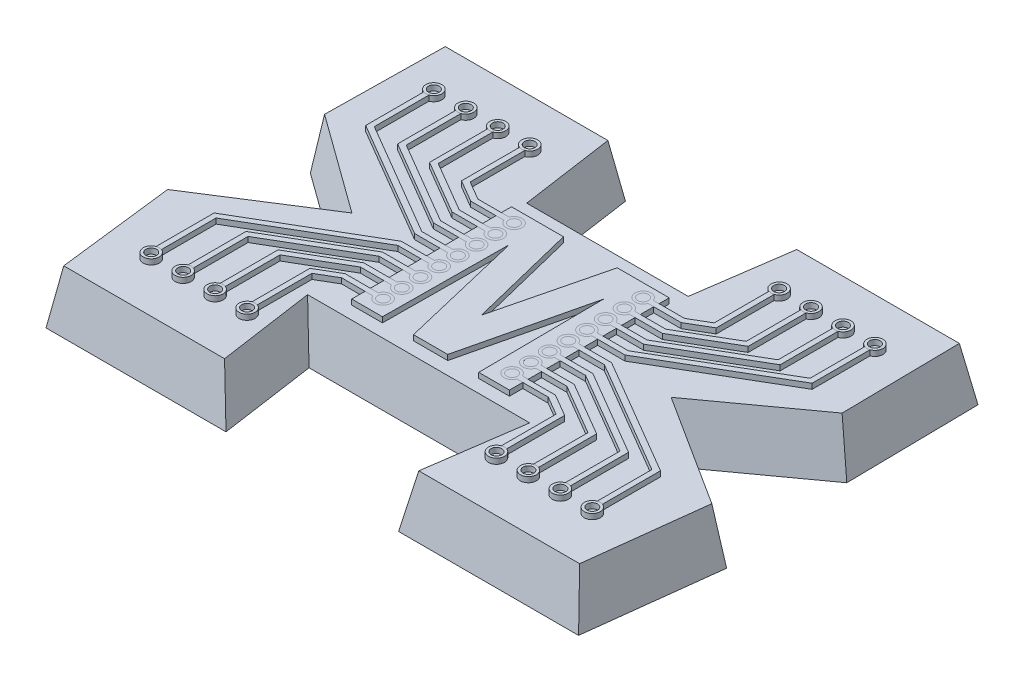
SolidWorks part; units mm, degrees
ref_plane "Спереди" through (0, 0, 0) normal (0, 0, 1) x (1, 0, 0)
ref_plane "Сверху" through (0, 0, 0) normal (0, 1, 0) x (1, 0, 0)
ref_plane "Справа" through (0, 0, 0) normal (1, 0, 0) x (0, 0, -1)
sketch "Эскиз1" plane through (0, 0, 0) normal (0, 1, 0) x (1, 0, 0)
  line L0 (0, 0) -> (-5.9483, 49.6449)
  line L1 (-5.9483, 49.6449) -> (33.7998, 75)
  line L2 (33.7998, 75) -> (-0.7287, 100.0053)
  line L3 (-0.7287, 100.0053) -> (0, 150)
  line L4 (0, 150) -> (67.5996, 150)
  line L5 (67.5996, 150) -> (72.7258, 114.3707)
  line L6 (72.7258, 114.3707) -> (127.2742, 114.3707)
  line L7 (0, 0) -> (67.5996, 0)
  line L8 (67.5996, 0) -> (62.3599, 36.418)
  line L9 (62.3599, 36.418) -> (137.6401, 36.418)
  line L10 (100, 114.3707) -> (100, 36.418) construction
  line L11 (33.7998, 0) -> (33.7998, 150) construction
  line L12 (166.2002, 0) -> (166.2002, 150) construction
  line L13 (132.4004, 0) -> (137.6401, 36.418)
  line L14 (200, 0) -> (132.4004, 0)
  line L15 (132.4004, 150) -> (127.2742, 114.3707)
  line L16 (200, 150) -> (132.4004, 150)
  line L17 (200.7287, 100.0053) -> (200, 150)
  line L18 (166.2002, 75) -> (200.7287, 100.0053)
  line L19 (205.9483, 49.6449) -> (166.2002, 75)
  line L20 (200, 0) -> (205.9483, 49.6449)
  dimension "D1" = 100
  dimension "D3" = 150
  dimension "D4" = 50
extrude "X" add sketch "Эскиз1" along normal blind 20 draft 10
sketch "Эскиз6" plane through (0, 20, 0) normal (0, 1, 0) x (1, 0, 0)
  line L0 (70, 104.8152) -> (70, 44.8152)
  line L1 (99.6154, 63.8897) -> (99.6154, 44.8152) construction
  line L2 (70, 44.8152) -> (81.5385, 44.8152)
  line L3 (81.5385, 44.8152) -> (81.9231, 92.0507)
  line L4 (81.9231, 92.0507) -> (93.1851, 44.8152)
  line L5 (70, 123.5265) -> (124.007, 123.5265) construction
  line L6 (93.1851, 44.8152) -> (106.0457, 44.8152)
  line L7 (106.0457, 44.8152) -> (117.3077, 92.0507)
  line L8 (117.3077, 92.0507) -> (117.6923, 44.8152)
  line L9 (117.6923, 44.8152) -> (129.2308, 44.8152)
  line L10 (129.2308, 44.8152) -> (129.2308, 104.8152)
  line L11 (70, 123.5265) -> (70, 26.4735) construction
  line L12 (70, 26.4735) -> (124.007, 26.4735) construction
  line L13 (129.2308, 104.8152) -> (109.7115, 104.8152)
  line L14 (109.7115, 104.8152) -> (99.6154, 63.8897)
  line L15 (99.6154, 63.8897) -> (89.5192, 104.8152)
  line L16 (89.5192, 104.8152) -> (70, 104.8152)
  line L17 (124.007, 123.5265) -> (124.007, 26.4735) construction
  line L18 (100, 39.9446) -> (100, 110.8442) construction
  line L19 (58.2897, 39.9446) -> (141.7103, 39.9446) construction
  line L20 (130.3296, 110.8442) -> (69.6704, 110.8442) construction
  point P9 (70, 74.8152)
  dimension "D1" = 19.5192
  dimension "D2" = 60
  dimension "D3" = 12.8606
  dimension "D4" = 11.5385
  dimension "D5" = 47.2356
  dimension "D6" = 13.877
  dimension "D7" = 13.877
  dimension "D8" = 27.716
  dimension "D9" = 90.467
  dimension "D10" = 90.467
  dimension "D11" = 30
extrude "M cut" cut sketch "Эскиз6" against normal blind 5
sketch "Эскиз8" plane through (0, 20, 0) normal (0, 1, 0) x (1, 0, 0)
  line L0 (3.2132, 128.4735) -> (17.1736, 128.4735) construction
  line L1 (17.1736, 128.4735) -> (53.1736, 128.4735) construction
  line L2 (53.1736, 128.4735) -> (67.1339, 128.4735) construction
  line L4 (64.5442, 146.4735) -> (3.4755, 146.4735) construction
  line L5 (3.4755, 146.4735) -> (2.8242, 101.7865) construction
  line L6 (100, 110.8442) -> (100, 39.9446) construction
  line L8 (58.2897, 39.9446) -> (141.7103, 39.9446) construction
  line L9 (3.1292, 3.5265) -> (63.5294, 3.5265) construction
  line L10 (17.1736, 128.4735) -> (29.1736, 128.4735) construction
  line L11 (130.3296, 110.8442) -> (69.6704, 110.8442) construction
  line L12 (17.1736, 22.3265) -> (29.1736, 22.3265) construction
  line L13 (53.1736, 22.3265) -> (196.753, 22.3265) construction
  line L14 (17.1736, 22.3265) -> (53.1736, 22.3265) construction
  line L15 (3.2132, 22.3265) -> (17.1736, 22.3265) construction
  line L16 (69.6704, 110.8442) -> (64.5442, 146.4735) construction
  circle A0 centre (17.1736, 128.4735) radius 3
  circle A1 centre (17.1736, 128.4735) radius 2
  circle A2 centre (29.1736, 128.4735) radius 2
  circle A3 centre (29.1736, 128.4735) radius 3
  circle A4 centre (41.1736, 128.4735) radius 2
  circle A5 centre (41.1736, 128.4735) radius 3
  circle A6 centre (53.1736, 128.4735) radius 2
  circle A7 centre (53.1736, 128.4735) radius 3
  circle A8 centre (182.8264, 22.3265) radius 3
  circle A9 centre (182.8264, 22.3265) radius 2
  circle A10 centre (170.8264, 22.3265) radius 2
  circle A11 centre (170.8264, 22.3265) radius 3
  circle A12 centre (158.8264, 22.3265) radius 2
  circle A13 centre (158.8264, 22.3265) radius 3
  circle A14 centre (146.8264, 22.3265) radius 2
  circle A15 centre (146.8264, 22.3265) radius 3
  circle A16 centre (53.1736, 22.3265) radius 3
  circle A17 centre (53.1736, 22.3265) radius 2
  circle A18 centre (41.1736, 22.3265) radius 3
  circle A19 centre (41.1736, 22.3265) radius 2
  circle A20 centre (29.1736, 22.3265) radius 3
  circle A21 centre (29.1736, 22.3265) radius 2
  circle A22 centre (17.1736, 22.3265) radius 2
  circle A23 centre (17.1736, 22.3265) radius 3
  circle A24 centre (146.8264, 128.4735) radius 3
  circle A25 centre (146.8264, 128.4735) radius 2
  circle A26 centre (158.8264, 128.4735) radius 3
  circle A27 centre (158.8264, 128.4735) radius 2
  circle A28 centre (170.8264, 128.4735) radius 3
  circle A29 centre (170.8264, 128.4735) radius 2
  circle A30 centre (182.8264, 128.4735) radius 2
  circle A31 centre (182.8264, 128.4735) radius 3
  circle A32 centre (13.3686, 14.8628) radius 2 [skipped]
  circle A33 centre (13.3686, 14.8628) radius 3 [skipped]
  circle A34 centre (25.3686, 14.8628) radius 2 [skipped]
  circle A35 centre (25.3686, 14.8628) radius 3 [skipped]
  circle A36 centre (37.3686, 14.8628) radius 2 [skipped]
  circle A37 centre (37.3686, 14.8628) radius 3 [skipped]
  circle A38 centre (49.3686, 14.8628) radius 2 [skipped]
  circle A39 centre (49.3686, 14.8628) radius 3 [skipped]
  dimension "D3" = 6
  dimension "D4" = 4
  dimension "D1" = 18
  dimension "D2" = 36
  dimension "D5" = 18.8
extrude "holes cut" cut sketch "Эскиз8" against normal blind 5
sketch "Эскиз9" plane through (0, 15, 0) normal (0, 1, 0) x (1, 0, 0)
  line L0 (75.7692, 44.8152) -> (75.7692, 104.8152) construction
  line L3 (100, 110.8442) -> (100, 39.9446) construction
  line L5 (58.2897, 39.9446) -> (141.7103, 39.9446) construction
  line L6 (130.3296, 110.8442) -> (69.6704, 110.8442) construction
  circle A0 centre (75.7692, 50.8152) radius 3
  circle A1 centre (75.7692, 50.8152) radius 2
  circle A2 centre (75.7692, 57.8416) radius 3
  circle A3 centre (75.7692, 57.8416) radius 2
  circle A4 centre (75.7692, 64.868) radius 3
  circle A5 centre (75.7692, 64.868) radius 2
  circle A6 centre (75.7692, 71.8944) radius 3
  circle A7 centre (75.7692, 71.8944) radius 2
  circle A8 centre (75.7692, 78.9208) radius 3
  circle A9 centre (75.7692, 78.9208) radius 2
  circle A10 centre (75.7692, 85.9472) radius 3
  circle A11 centre (75.7692, 85.9472) radius 2
  circle A12 centre (75.7692, 92.9736) radius 3
  circle A13 centre (75.7692, 92.9736) radius 2
  circle A14 centre (75.7692, 100) radius 3
  circle A15 centre (75.7692, 100) radius 2
  circle A16 centre (124.2308, 100) radius 2
  circle A17 centre (124.2308, 100) radius 3
  circle A18 centre (124.2308, 92.9736) radius 2
  circle A19 centre (124.2308, 92.9736) radius 3
  circle A20 centre (124.2308, 85.9472) radius 2
  circle A21 centre (124.2308, 85.9472) radius 3
  circle A22 centre (124.2308, 78.9208) radius 2
  circle A23 centre (124.2308, 78.9208) radius 3
  circle A24 centre (124.2308, 71.8944) radius 2
  circle A25 centre (124.2308, 71.8944) radius 3
  circle A26 centre (124.2308, 64.868) radius 2
  circle A27 centre (124.2308, 64.868) radius 3
  circle A28 centre (124.2308, 57.8416) radius 2
  circle A29 centre (124.2308, 57.8416) radius 3
  circle A30 centre (124.2308, 50.8152) radius 2
  circle A31 centre (124.2308, 50.8152) radius 3
  dimension "D2" = 4
  dimension "D3" = 6
extrude "M holes" add sketch "Эскиз9" along normal blind 7 separate body
sketch "Эскиз10" plane through (0, 20, 0) normal (0, 1, 0) x (1, 0, 0)
  line L0 (17.1736, 128.4735) -> (17.1736, 104.4969) construction
  line L1 (17.1736, 104.4969) -> (60.8535, 78.9208) construction
  line L2 (60.8535, 78.9208) -> (75.7692, 78.9208) construction
  line L3 (29.1736, 128.4735) -> (29.1736, 104.4969) construction
  line L4 (29.1736, 104.4969) -> (60.8535, 85.9472) construction
  line L5 (60.8535, 85.9472) -> (75.7692, 85.9472) construction
  line L6 (75.7692, 92.9736) -> (60.8535, 92.9736) construction
  line L7 (60.8535, 92.9736) -> (41.1736, 104.4969) construction
  line L8 (41.1736, 104.4969) -> (41.1736, 128.4735) construction
  line L9 (53.1736, 128.4735) -> (53.1736, 104.4969) construction
  line L10 (53.1736, 104.4969) -> (60.8535, 100) construction
  line L11 (60.8535, 100) -> (75.7692, 100) construction
  line L12 (72.9408, 79.9208) -> (72.9408, 77.9208) construction
  line L13 (72.9408, 84.9472) -> (72.9408, 86.9472) construction
  line L14 (72.9408, 91.9736) -> (72.9408, 93.9736) construction
  line L15 (72.9408, 99) -> (72.9408, 101) construction
  line L16 (16.1736, 125.645) -> (18.1736, 125.645) construction
  line L17 (28.1736, 125.645) -> (30.1736, 125.645) construction
  line L18 (40.1736, 125.645) -> (42.1736, 125.645) construction
  line L19 (54.1736, 125.645) -> (52.1736, 125.645) construction
  line L20 (18.1736, 105.118) -> (61.2064, 79.9208)
  line L21 (30.1736, 105.1144) -> (61.2004, 86.9472)
  line L22 (60.5006, 77.9208) -> (16.1736, 103.8758)
  line L23 (18.1736, 125.645) -> (18.1736, 105.118)
  line L24 (61.2064, 79.9208) -> (72.9408, 79.9208)
  line L25 (72.9408, 77.9208) -> (60.5006, 77.9208)
  line L26 (16.1736, 125.645) -> (16.1736, 103.8758)
  line L27 (30.1736, 105.1144) -> (30.1736, 125.645)
  line L28 (60.5067, 84.9472) -> (28.1736, 103.8794)
  line L29 (28.1736, 125.645) -> (28.1736, 103.8794)
  line L30 (72.9408, 86.9472) -> (61.2004, 86.9472)
  line L31 (72.9408, 84.9472) -> (60.5067, 84.9472)
  line L32 (42.1736, 105.1223) -> (61.2138, 93.9736)
  line L33 (60.4933, 91.9736) -> (40.1736, 103.8715)
  line L34 (42.1736, 125.645) -> (42.1736, 105.1223)
  line L35 (40.1736, 125.645) -> (40.1736, 103.8715)
  line L36 (61.2138, 93.9736) -> (72.9408, 93.9736)
  line L37 (72.9408, 91.9736) -> (60.4933, 91.9736)
  line L38 (54.1736, 105.1174) -> (61.2054, 101)
  line L39 (60.5017, 99) -> (52.1736, 103.8764)
  line L40 (52.1736, 103.8764) -> (52.1736, 125.645)
  line L41 (54.1736, 125.645) -> (54.1736, 105.1174)
  line L42 (61.2054, 101) -> (72.9408, 101)
  line L43 (72.9408, 99) -> (60.5017, 99)
  line L44 (16.1736, 103.8758) -> (18.1736, 105.118) construction
  line L45 (28.1736, 103.8794) -> (30.1736, 105.1144) construction
  line L46 (40.1736, 103.8715) -> (42.1736, 105.1223) construction
  line L47 (52.1736, 103.8764) -> (54.1736, 105.1174) construction
  line L48 (60.5017, 99) -> (61.2054, 101) construction
  line L49 (60.4933, 91.9736) -> (61.2138, 93.9736) construction
  line L50 (60.5067, 84.9472) -> (61.2004, 86.9472) construction
  line L51 (60.5006, 77.9208) -> (61.2064, 79.9208) construction
  line L52 (100, 110.8442) -> (100, 39.9446) construction
  line L53 (130.3296, 110.8442) -> (69.6704, 110.8442) construction
  line L54 (58.2897, 39.9446) -> (141.7103, 39.9446) construction
  line L55 (75.7692, 78.9208) -> (75.7692, 71.8944) construction
  line L56 (75.7692, 75.4076) -> (100, 75.4076) construction
  line L57 (139.4994, 77.9208) -> (138.7936, 79.9208) construction
  line L58 (139.4933, 84.9472) -> (138.7996, 86.9472) construction
  line L59 (139.5067, 91.9736) -> (138.7862, 93.9736) construction
  line L60 (139.4983, 99) -> (138.7946, 101) construction
  line L61 (147.8264, 103.8764) -> (145.8264, 105.1174) construction
  line L62 (159.8264, 103.8715) -> (157.8264, 105.1223) construction
  line L63 (171.8264, 103.8794) -> (169.8264, 105.1144) construction
  line L64 (183.8264, 103.8758) -> (181.8264, 105.118) construction
  line L65 (145.8264, 125.645) -> (147.8264, 125.645) construction
  line L66 (159.8264, 125.645) -> (157.8264, 125.645) construction
  line L67 (171.8264, 125.645) -> (169.8264, 125.645) construction
  line L68 (183.8264, 125.645) -> (181.8264, 125.645) construction
  line L69 (127.0592, 99) -> (127.0592, 101) construction
  line L70 (127.0592, 91.9736) -> (127.0592, 93.9736) construction
  line L71 (127.0592, 84.9472) -> (127.0592, 86.9472) construction
  line L72 (127.0592, 79.9208) -> (127.0592, 77.9208) construction
  line L73 (139.1465, 100) -> (124.2308, 100) construction
  line L74 (146.8264, 104.4969) -> (139.1465, 100) construction
  line L75 (146.8264, 128.4735) -> (146.8264, 104.4969) construction
  line L76 (158.8264, 104.4969) -> (158.8264, 128.4735) construction
  line L77 (139.1465, 92.9736) -> (158.8264, 104.4969) construction
  line L78 (124.2308, 92.9736) -> (139.1465, 92.9736) construction
  line L79 (139.1465, 85.9472) -> (124.2308, 85.9472) construction
  line L80 (170.8264, 104.4969) -> (139.1465, 85.9472) construction
  line L81 (170.8264, 128.4735) -> (170.8264, 104.4969) construction
  line L82 (139.1465, 78.9208) -> (124.2308, 78.9208) construction
  line L83 (182.8264, 104.4969) -> (139.1465, 78.9208) construction
  line L84 (182.8264, 128.4735) -> (182.8264, 104.4969) construction
  line L85 (127.0592, 99) -> (139.4983, 99)
  line L86 (138.7946, 101) -> (127.0592, 101)
  line L87 (145.8264, 125.645) -> (145.8264, 105.1174)
  line L88 (147.8264, 103.8764) -> (147.8264, 125.645)
  line L89 (139.4983, 99) -> (147.8264, 103.8764)
  line L90 (145.8264, 105.1174) -> (138.7946, 101)
  line L91 (127.0592, 91.9736) -> (139.5067, 91.9736)
  line L92 (138.7862, 93.9736) -> (127.0592, 93.9736)
  line L93 (159.8264, 125.645) -> (159.8264, 103.8715)
  line L94 (157.8264, 125.645) -> (157.8264, 105.1223)
  line L95 (139.5067, 91.9736) -> (159.8264, 103.8715)
  line L96 (157.8264, 105.1223) -> (138.7862, 93.9736)
  line L97 (127.0592, 84.9472) -> (139.4933, 84.9472)
  line L98 (127.0592, 86.9472) -> (138.7996, 86.9472)
  line L99 (171.8264, 125.645) -> (171.8264, 103.8794)
  line L100 (139.4933, 84.9472) -> (171.8264, 103.8794)
  line L101 (169.8264, 105.1144) -> (169.8264, 125.645)
  line L102 (183.8264, 125.645) -> (183.8264, 103.8758)
  line L103 (127.0592, 77.9208) -> (139.4994, 77.9208)
  line L104 (138.7936, 79.9208) -> (127.0592, 79.9208)
  line L105 (181.8264, 125.645) -> (181.8264, 105.118)
  line L106 (139.4994, 77.9208) -> (183.8264, 103.8758)
  line L107 (169.8264, 105.1144) -> (138.7996, 86.9472)
  line L108 (181.8264, 105.118) -> (138.7936, 79.9208)
  line L109 (182.8264, 22.3417) -> (182.8264, 46.3183) construction
  line L110 (182.8264, 46.3183) -> (139.1465, 71.8944) construction
  line L111 (139.1465, 71.8944) -> (124.2308, 71.8944) construction
  line L112 (170.8264, 22.3417) -> (170.8264, 46.3183) construction
  line L113 (170.8264, 46.3183) -> (139.1465, 64.868) construction
  line L114 (139.1465, 64.868) -> (124.2308, 64.868) construction
  line L115 (124.2308, 57.8416) -> (139.1465, 57.8416) construction
  line L116 (139.1465, 57.8416) -> (158.8264, 46.3183) construction
  line L117 (158.8264, 46.3183) -> (158.8264, 22.3417) construction
  line L118 (146.8264, 22.3417) -> (146.8264, 46.3183) construction
  line L119 (146.8264, 46.3183) -> (139.1465, 50.8152) construction
  line L120 (139.1465, 50.8152) -> (124.2308, 50.8152) construction
  line L121 (127.0592, 70.8944) -> (127.0592, 72.8944) construction
  line L122 (127.0592, 65.868) -> (127.0592, 63.868) construction
  line L123 (127.0592, 58.8416) -> (127.0592, 56.8416) construction
  line L124 (127.0592, 51.8152) -> (127.0592, 49.8152) construction
  line L125 (183.8264, 25.1701) -> (181.8264, 25.1701) construction
  line L126 (171.8264, 25.1701) -> (169.8264, 25.1701) construction
  line L127 (159.8264, 25.1701) -> (157.8264, 25.1701) construction
  line L128 (145.8264, 25.1701) -> (147.8264, 25.1701) construction
  line L129 (183.8264, 46.9394) -> (181.8264, 45.6972) construction
  line L130 (171.8264, 46.9358) -> (169.8264, 45.7007) construction
  line L131 (159.8264, 46.9437) -> (157.8264, 45.6928) construction
  line L132 (147.8264, 46.9388) -> (145.8264, 45.6978) construction
  line L133 (139.4983, 51.8152) -> (138.7946, 49.8152) construction
  line L134 (139.5067, 58.8416) -> (138.7862, 56.8416) construction
  line L135 (139.4933, 65.868) -> (138.7996, 63.868) construction
  line L136 (139.4994, 72.8944) -> (138.7936, 70.8944) construction
  line L137 (60.5006, 72.8944) -> (61.2064, 70.8944) construction
  line L138 (60.5067, 65.868) -> (61.2004, 63.868) construction
  line L139 (60.4933, 58.8416) -> (61.2138, 56.8416) construction
  line L140 (60.5017, 51.8152) -> (61.2054, 49.8152) construction
  line L141 (52.1736, 46.9388) -> (54.1736, 45.6978) construction
  line L142 (40.1736, 46.9437) -> (42.1736, 45.6928) construction
  line L143 (28.1736, 46.9358) -> (30.1736, 45.7007) construction
  line L144 (16.1736, 46.9394) -> (18.1736, 45.6972) construction
  line L145 (54.1736, 25.1701) -> (52.1736, 25.1701) construction
  line L146 (40.1736, 25.1701) -> (42.1736, 25.1701) construction
  line L147 (28.1736, 25.1701) -> (30.1736, 25.1701) construction
  line L148 (16.1736, 25.1701) -> (18.1736, 25.1701) construction
  line L149 (72.9408, 51.8152) -> (72.9408, 49.8152) construction
  line L150 (72.9408, 58.8416) -> (72.9408, 56.8416) construction
  line L151 (72.9408, 65.868) -> (72.9408, 63.868) construction
  line L152 (72.9408, 70.8944) -> (72.9408, 72.8944) construction
  line L153 (60.8535, 50.8152) -> (75.7692, 50.8152) construction
  line L154 (53.1736, 46.3183) -> (60.8535, 50.8152) construction
  line L155 (53.1736, 22.3417) -> (53.1736, 46.3183) construction
  line L156 (41.1736, 46.3183) -> (41.1736, 22.3417) construction
  line L157 (60.8535, 57.8416) -> (41.1736, 46.3183) construction
  line L158 (75.7692, 57.8416) -> (60.8535, 57.8416) construction
  line L159 (60.8535, 64.868) -> (75.7692, 64.868) construction
  line L160 (29.1736, 46.3183) -> (60.8535, 64.868) construction
  line L161 (29.1736, 22.3417) -> (29.1736, 46.3183) construction
  line L162 (60.8535, 71.8944) -> (75.7692, 71.8944) construction
  line L163 (17.1736, 46.3183) -> (60.8535, 71.8944) construction
  line L164 (17.1736, 22.3417) -> (17.1736, 46.3183) construction
  line L165 (181.8264, 45.6972) -> (138.7936, 70.8944)
  line L166 (169.8264, 45.7007) -> (138.7996, 63.868)
  line L167 (139.4994, 72.8944) -> (183.8264, 46.9394)
  line L168 (181.8264, 25.1701) -> (181.8264, 45.6972)
  line L169 (138.7936, 70.8944) -> (127.0592, 70.8944)
  line L170 (127.0592, 72.8944) -> (139.4994, 72.8944)
  line L171 (183.8264, 25.1701) -> (183.8264, 46.9394)
  line L172 (169.8264, 45.7007) -> (169.8264, 25.1701)
  line L173 (139.4933, 65.868) -> (171.8264, 46.9358)
  line L174 (171.8264, 25.1701) -> (171.8264, 46.9358)
  line L175 (127.0592, 63.868) -> (138.7996, 63.868)
  line L176 (127.0592, 65.868) -> (139.4933, 65.868)
  line L177 (157.8264, 45.6928) -> (138.7862, 56.8416)
  line L178 (139.5067, 58.8416) -> (159.8264, 46.9437)
  line L179 (157.8264, 25.1701) -> (157.8264, 45.6928)
  line L180 (159.8264, 25.1701) -> (159.8264, 46.9437)
  line L181 (138.7862, 56.8416) -> (127.0592, 56.8416)
  line L182 (127.0592, 58.8416) -> (139.5067, 58.8416)
  line L183 (145.8264, 45.6978) -> (138.7946, 49.8152)
  line L184 (139.4983, 51.8152) -> (147.8264, 46.9388)
  line L185 (147.8264, 46.9388) -> (147.8264, 25.1701)
  line L186 (145.8264, 25.1701) -> (145.8264, 45.6978)
  line L187 (138.7946, 49.8152) -> (127.0592, 49.8152)
  line L188 (127.0592, 51.8152) -> (139.4983, 51.8152)
  line L189 (72.9408, 51.8152) -> (60.5017, 51.8152)
  line L190 (61.2054, 49.8152) -> (72.9408, 49.8152)
  line L191 (54.1736, 25.1701) -> (54.1736, 45.6978)
  line L192 (52.1736, 46.9388) -> (52.1736, 25.1701)
  line L193 (60.5017, 51.8152) -> (52.1736, 46.9388)
  line L194 (54.1736, 45.6978) -> (61.2054, 49.8152)
  line L195 (72.9408, 58.8416) -> (60.4933, 58.8416)
  line L196 (61.2138, 56.8416) -> (72.9408, 56.8416)
  line L197 (40.1736, 25.1701) -> (40.1736, 46.9437)
  line L198 (42.1736, 25.1701) -> (42.1736, 45.6928)
  line L199 (60.4933, 58.8416) -> (40.1736, 46.9437)
  line L200 (42.1736, 45.6928) -> (61.2138, 56.8416)
  line L201 (72.9408, 65.868) -> (60.5067, 65.868)
  line L202 (72.9408, 63.868) -> (61.2004, 63.868)
  line L203 (28.1736, 25.1701) -> (28.1736, 46.9358)
  line L204 (60.5067, 65.868) -> (28.1736, 46.9358)
  line L205 (30.1736, 45.7007) -> (30.1736, 25.1701)
  line L206 (16.1736, 25.1701) -> (16.1736, 46.9394)
  line L207 (72.9408, 72.8944) -> (60.5006, 72.8944)
  line L208 (61.2064, 70.8944) -> (72.9408, 70.8944)
  line L209 (18.1736, 25.1701) -> (18.1736, 45.6972)
  line L210 (60.5006, 72.8944) -> (16.1736, 46.9394)
  line L211 (30.1736, 45.7007) -> (61.2004, 63.868)
  line L212 (18.1736, 45.6972) -> (61.2064, 70.8944)
  arc A0 (16.1736, 125.645) -> (18.1736, 125.645) centre (17.1736, 128.4735) ccw
  arc A1 (28.1736, 125.645) -> (30.1736, 125.645) centre (29.1736, 128.4735) ccw
  arc A3 (40.1736, 125.645) -> (42.1736, 125.645) centre (41.1736, 128.4735) ccw
  arc A4 (52.1736, 125.645) -> (54.1736, 125.645) centre (53.1736, 128.4735) ccw
  arc A9 (72.9408, 101) -> (72.9408, 99) centre (75.7692, 100) ccw
  arc A11 (72.9408, 91.9736) -> (72.9408, 93.9736) centre (75.7692, 92.9736) cw
  arc A13 (72.9408, 86.9472) -> (72.9408, 84.9472) centre (75.7692, 85.9472) ccw
  arc A15 (72.9408, 77.9208) -> (72.9408, 79.9208) centre (75.7692, 78.9208) cw
  arc A16 (127.0592, 77.9208) -> (127.0592, 79.9208) centre (124.2308, 78.9208) ccw
  arc A26 (127.0592, 86.9472) -> (127.0592, 84.9472) centre (124.2308, 85.9472) cw
  arc A27 (127.0592, 91.9736) -> (127.0592, 93.9736) centre (124.2308, 92.9736) ccw
  arc A28 (127.0592, 101) -> (127.0592, 99) centre (124.2308, 100) cw
  arc A29 (147.8264, 125.645) -> (145.8264, 125.645) centre (146.8264, 128.4735) cw
  arc A30 (159.8264, 125.645) -> (157.8264, 125.645) centre (158.8264, 128.4735) cw
  arc A31 (171.8264, 125.645) -> (169.8264, 125.645) centre (170.8264, 128.4735) cw
  arc A32 (183.8264, 125.645) -> (181.8264, 125.645) centre (182.8264, 128.4735) cw
  arc A33 (183.8264, 25.1701) -> (181.8264, 25.1701) centre (182.8264, 22.3417) ccw
  arc A34 (171.8264, 25.1701) -> (169.8264, 25.1701) centre (170.8264, 22.3417) ccw
  arc A35 (159.8264, 25.1701) -> (157.8264, 25.1701) centre (158.8264, 22.3417) ccw
  arc A36 (147.8264, 25.1701) -> (145.8264, 25.1701) centre (146.8264, 22.3417) ccw
  arc A37 (127.0592, 49.8152) -> (127.0592, 51.8152) centre (124.2308, 50.8152) ccw
  arc A38 (127.0592, 58.8416) -> (127.0592, 56.8416) centre (124.2308, 57.8416) cw
  arc A39 (127.0592, 63.868) -> (127.0592, 65.868) centre (124.2308, 64.868) ccw
  arc A40 (127.0592, 72.8944) -> (127.0592, 70.8944) centre (124.2308, 71.8944) cw
  arc A41 (72.9408, 72.8944) -> (72.9408, 70.8944) centre (75.7692, 71.8944) ccw
  arc A42 (72.9408, 63.868) -> (72.9408, 65.868) centre (75.7692, 64.868) cw
  arc A43 (72.9408, 58.8416) -> (72.9408, 56.8416) centre (75.7692, 57.8416) ccw
  arc A44 (72.9408, 49.8152) -> (72.9408, 51.8152) centre (75.7692, 50.8152) cw
  arc A45 (52.1736, 25.1701) -> (54.1736, 25.1701) centre (53.1736, 22.3417) cw
  arc A46 (40.1736, 25.1701) -> (42.1736, 25.1701) centre (41.1736, 22.3417) cw
  arc A47 (28.1736, 25.1701) -> (30.1736, 25.1701) centre (29.1736, 22.3417) cw
  arc A48 (16.1736, 25.1701) -> (18.1736, 25.1701) centre (17.1736, 22.3417) cw
  circle A49 centre (75.7692, 100) radius 3 construction
  circle A50 centre (29.1736, 128.4735) radius 3 construction
  circle A51 centre (29.1736, 128.4735) radius 3 construction
  dimension "D1" = 2
  dimension "D2" = 2
extrude "routes" add sketch "Эскиз10" along normal blind 2 and the other way blind 5
sketch "Эскиз11" plane through (0, 15, 0) normal (0, 1, 0) x (1, 0, 0)
  line L0 (81.9231, 92.0507) -> (81.5385, 44.8152)
  line L1 (81.5385, 44.8152) -> (70, 44.8152)
  line L2 (70, 44.8152) -> (70, 49.8152)
  line L3 (70, 49.8152) -> (72.9408, 49.8152)
  line L4 (81.9231, 92.0507) -> (93.1851, 44.8152)
  line L5 (93.1851, 44.8152) -> (106.0457, 44.8152)
  line L6 (106.0457, 44.8152) -> (117.3077, 92.0507)
  line L7 (117.3077, 92.0507) -> (117.6923, 44.8152)
  line L8 (117.6923, 44.8152) -> (129.2308, 44.8152)
  line L9 (129.2308, 44.8152) -> (129.2308, 49.8152)
  line L10 (129.2308, 49.8152) -> (127.0592, 49.8152)
  line L11 (129.2308, 101) -> (129.2308, 104.8152)
  line L12 (129.2308, 104.8152) -> (109.7115, 104.8152)
  line L13 (109.7115, 104.8152) -> (99.6154, 63.8897)
  line L14 (99.6154, 63.8897) -> (89.5192, 104.8152)
  line L15 (89.5192, 104.8152) -> (70, 104.8152)
  line L16 (70, 104.8152) -> (70, 101)
  line L17 (70, 101) -> (72.9408, 101)
  line L18 (72.9408, 99) -> (70, 99)
  line L19 (70, 99) -> (70, 93.9736)
  line L20 (70, 93.9736) -> (72.9408, 93.9736)
  line L21 (70, 91.9736) -> (70, 86.9472)
  line L22 (70, 86.9472) -> (72.9408, 86.9472)
  line L23 (60.5067, 84.9472) -> (72.9408, 84.9472) construction
  line L24 (70, 84.9472) -> (72.9408, 84.9472)
  line L25 (72.9408, 91.9736) -> (70, 91.9736)
  line L26 (70, 84.9472) -> (70, 79.9208)
  line L27 (70, 79.9208) -> (72.9408, 79.9208)
  line L28 (72.9408, 77.9208) -> (70, 77.9208)
  line L29 (70, 77.9208) -> (70, 72.8944)
  line L30 (70, 72.8944) -> (72.9408, 72.8944)
  line L31 (72.9408, 70.8944) -> (70, 70.8944)
  line L32 (70, 70.8944) -> (70, 65.868)
  line L33 (70, 65.868) -> (72.9408, 65.868)
  line L34 (72.9408, 63.868) -> (70, 63.868)
  line L35 (70, 63.868) -> (70, 58.8416)
  line L36 (70, 58.8416) -> (72.9408, 58.8416)
  line L37 (72.9408, 56.8416) -> (70, 56.8416)
  line L38 (70, 56.8416) -> (70, 51.8152)
  line L39 (70, 51.8152) -> (72.9408, 51.8152)
  line L40 (127.0592, 99) -> (129.2308, 99)
  line L41 (129.2308, 99) -> (129.2308, 93.9736)
  line L42 (129.2308, 93.9736) -> (127.0592, 93.9736)
  line L43 (127.0592, 91.9736) -> (129.2308, 91.9736)
  line L44 (129.2308, 91.9736) -> (129.2308, 86.9472)
  line L45 (129.2308, 86.9472) -> (127.0592, 86.9472)
  line L46 (127.0592, 101) -> (129.2308, 101)
  line L47 (127.0592, 84.9472) -> (129.2308, 84.9472)
  line L48 (129.2308, 84.9472) -> (129.2308, 79.9208)
  line L49 (129.2308, 79.9208) -> (127.0592, 79.9208)
  line L50 (127.0592, 77.9208) -> (129.2308, 77.9208)
  line L51 (129.2308, 77.9208) -> (129.2308, 72.8944)
  line L52 (129.2308, 72.8944) -> (127.0592, 72.8944)
  line L53 (127.0592, 70.8944) -> (129.2308, 70.8944)
  line L54 (129.2308, 70.8944) -> (129.2308, 65.868)
  line L55 (129.2308, 65.868) -> (127.0592, 65.868)
  line L56 (127.0592, 63.868) -> (129.2308, 63.868)
  line L57 (129.2308, 63.868) -> (129.2308, 58.8416)
  line L58 (129.2308, 58.8416) -> (127.0592, 58.8416)
  line L59 (127.0592, 56.8416) -> (129.2308, 56.8416)
  line L60 (129.2308, 56.8416) -> (129.2308, 51.8152)
  line L61 (129.2308, 51.8152) -> (127.0592, 51.8152)
  arc A0 (72.9408, 99) -> (72.9408, 101) centre (75.7692, 100) ccw
  arc A1 (72.9408, 99) -> (72.9408, 101) centre (75.7692, 100) ccw construction
  arc A2 (72.9408, 91.9736) -> (72.9408, 93.9736) centre (75.7692, 92.9736) ccw
  circle A3 centre (75.7692, 92.9736) radius 3 construction
  arc A4 (72.9408, 86.9472) -> (72.9408, 84.9472) centre (75.7692, 85.9472) cw
  circle A5 centre (75.7692, 85.9472) radius 3 construction
  arc A6 (72.9408, 79.9208) -> (72.9408, 77.9208) centre (75.7692, 78.9208) cw
  arc A7 (72.9408, 77.9208) -> (72.9408, 79.9208) centre (75.7692, 78.9208) ccw construction
  arc A8 (72.9408, 72.8944) -> (72.9408, 70.8944) centre (75.7692, 71.8944) cw
  arc A9 (72.9408, 70.8944) -> (72.9408, 72.8944) centre (75.7692, 71.8944) ccw construction
  arc A10 (72.9408, 65.868) -> (72.9408, 63.868) centre (75.7692, 64.868) cw
  arc A11 (72.9408, 63.868) -> (72.9408, 65.868) centre (75.7692, 64.868) ccw construction
  arc A12 (72.9408, 56.8416) -> (72.9408, 58.8416) centre (75.7692, 57.8416) ccw
  arc A13 (72.9408, 56.8416) -> (72.9408, 58.8416) centre (75.7692, 57.8416) ccw construction
  arc A14 (72.9408, 51.8152) -> (72.9408, 49.8152) centre (75.7692, 50.8152) cw
  arc A15 (72.9408, 49.8152) -> (72.9408, 51.8152) centre (75.7692, 50.8152) ccw construction
  circle A16 centre (75.7692, 57.8416) radius 3 construction
  arc A17 (72.9408, 91.9736) -> (72.9408, 93.9736) centre (75.7692, 92.9736) ccw construction
  circle A18 centre (75.7692, 100) radius 3 construction
  arc A19 (127.0592, 101) -> (127.0592, 99) centre (124.2308, 100) ccw
  arc A20 (127.0592, 101) -> (127.0592, 99) centre (124.2308, 100) ccw construction
  arc A21 (127.0592, 91.9736) -> (127.0592, 93.9736) centre (124.2308, 92.9736) cw
  circle A22 centre (124.2308, 92.9736) radius 3 construction
  arc A23 (127.0592, 86.9472) -> (127.0592, 84.9472) centre (124.2308, 85.9472) ccw
  arc A24 (127.0592, 86.9472) -> (127.0592, 84.9472) centre (124.2308, 85.9472) ccw construction
  arc A25 (127.0592, 77.9208) -> (127.0592, 79.9208) centre (124.2308, 78.9208) cw
  circle A26 centre (124.2308, 78.9208) radius 3 construction
  arc A27 (127.0592, 72.8944) -> (127.0592, 70.8944) centre (124.2308, 71.8944) ccw
  circle A28 centre (124.2308, 71.8944) radius 3 construction
  arc A29 (127.0592, 65.868) -> (127.0592, 63.868) centre (124.2308, 64.868) ccw
  arc A30 (127.0592, 65.868) -> (127.0592, 63.868) centre (124.2308, 64.868) ccw construction
  arc A31 (127.0592, 58.8416) -> (127.0592, 56.8416) centre (124.2308, 57.8416) ccw
  arc A32 (127.0592, 58.8416) -> (127.0592, 56.8416) centre (124.2308, 57.8416) ccw construction
  arc A33 (127.0592, 51.8152) -> (127.0592, 49.8152) centre (124.2308, 50.8152) ccw
  circle A34 centre (124.2308, 50.8152) radius 3 construction
  arc A35 (127.0592, 79.9208) -> (127.0592, 77.9208) centre (124.2308, 78.9208) ccw construction
  circle A36 centre (75.7692, 100) radius 2
  circle A37 centre (75.7692, 92.9736) radius 2
  circle A38 centre (75.7692, 85.9472) radius 2
  circle A39 centre (75.7692, 78.9208) radius 2
  circle A40 centre (75.7692, 71.8944) radius 2
  circle A41 centre (75.7692, 64.868) radius 2
  circle A42 centre (75.7692, 57.8416) radius 2
  circle A43 centre (75.7692, 50.8152) radius 2
  circle A44 centre (124.2308, 100) radius 2
  circle A45 centre (124.2308, 92.9736) radius 2
  circle A46 centre (124.2308, 85.9472) radius 2
  circle A47 centre (124.2308, 78.9208) radius 2
  circle A48 centre (124.2308, 71.8944) radius 2
  circle A49 centre (124.2308, 64.868) radius 2
  circle A50 centre (124.2308, 50.8152) radius 2
  circle A51 centre (124.2308, 57.8416) radius 2
  circle A52 centre (124.2308, 57.8416) radius 2 construction
  circle A53 centre (124.2308, 50.8152) radius 2 construction
  circle A54 centre (124.2308, 64.868) radius 2 construction
  circle A55 centre (124.2308, 71.8944) radius 2 construction
  circle A56 centre (124.2308, 78.9208) radius 2 construction
  circle A58 centre (124.2308, 85.9472) radius 2 construction
  circle A59 centre (124.2308, 92.9736) radius 2 construction
  circle A60 centre (124.2308, 100) radius 2 construction
  circle A61 centre (75.7692, 100) radius 2 construction
  circle A62 centre (75.7692, 92.9736) radius 2 construction
  circle A63 centre (75.7692, 85.9472) radius 2 construction
  circle A64 centre (75.7692, 78.9208) radius 2 construction
  circle A65 centre (75.7692, 71.8944) radius 2 construction
  circle A66 centre (75.7692, 64.868) radius 2 construction
  circle A67 centre (75.7692, 57.8416) radius 2 construction
  circle A68 centre (75.7692, 50.8152) radius 2 construction
extrude "M" add sketch "Эскиз11" along normal blind 7 separate body
sketch "Эскиз14" plane through (0, 15, 0) normal (0, 1, 0) x (1, 0, 0)
  line L0 (75.7692, 78.9208) -> (75.7692, 71.8944) construction
  line L1 (75.7692, 75.4076) -> (93.0186, 75.4076) construction
  line L3 (100, 110.8442) -> (100, 39.9446) construction
  line L5 (130.3296, 110.8442) -> (69.6704, 110.8442) construction
  line L6 (58.2897, 39.9446) -> (141.7103, 39.9446) construction
  circle A0 centre (17.1736, 128.4735) radius 2
  circle A1 centre (17.1736, 128.4735) radius 3
  circle A2 centre (29.1736, 128.4735) radius 2
  circle A3 centre (29.1736, 128.4735) radius 3
  circle A4 centre (41.1736, 128.4735) radius 2
  circle A5 centre (41.1736, 128.4735) radius 3
  circle A6 centre (53.1736, 128.4735) radius 2
  circle A7 centre (53.1736, 128.4735) radius 3
  circle A8 centre (146.8264, 128.4735) radius 3
  circle A10 centre (146.8264, 128.4735) radius 2
  circle A11 centre (158.8264, 128.4735) radius 3
  circle A12 centre (158.8264, 128.4735) radius 2
  circle A13 centre (170.8264, 128.4735) radius 3
  circle A14 centre (170.8264, 128.4735) radius 2
  circle A15 centre (182.8264, 128.4735) radius 3
  circle A16 centre (182.8264, 128.4735) radius 2
  circle A17 centre (182.8264, 22.3417) radius 2
  circle A18 centre (182.8264, 22.3417) radius 3
  circle A19 centre (170.8264, 22.3417) radius 2
  circle A20 centre (170.8264, 22.3417) radius 3
  circle A21 centre (158.8264, 22.3417) radius 2
  circle A22 centre (158.8264, 22.3417) radius 3
  circle A23 centre (146.8264, 22.3417) radius 2
  circle A24 centre (146.8264, 22.3417) radius 3
  circle A25 centre (53.1736, 22.3417) radius 3
  circle A26 centre (53.1736, 22.3417) radius 2
  circle A27 centre (41.1736, 22.3417) radius 3
  circle A28 centre (41.1736, 22.3417) radius 2
  circle A29 centre (29.1736, 22.3417) radius 3
  circle A30 centre (29.1736, 22.3417) radius 2
  circle A31 centre (17.1736, 22.3417) radius 3
  circle A32 centre (17.1736, 22.3417) radius 2
  point P20 (75.7692, 75.4076)
extrude "holes" add sketch "Эскиз14" along normal blind 7 separate body
equation "\"D1@Эскиз10\" = \"d\""
equation "\"D2@Эскиз10\" = \"d\""
